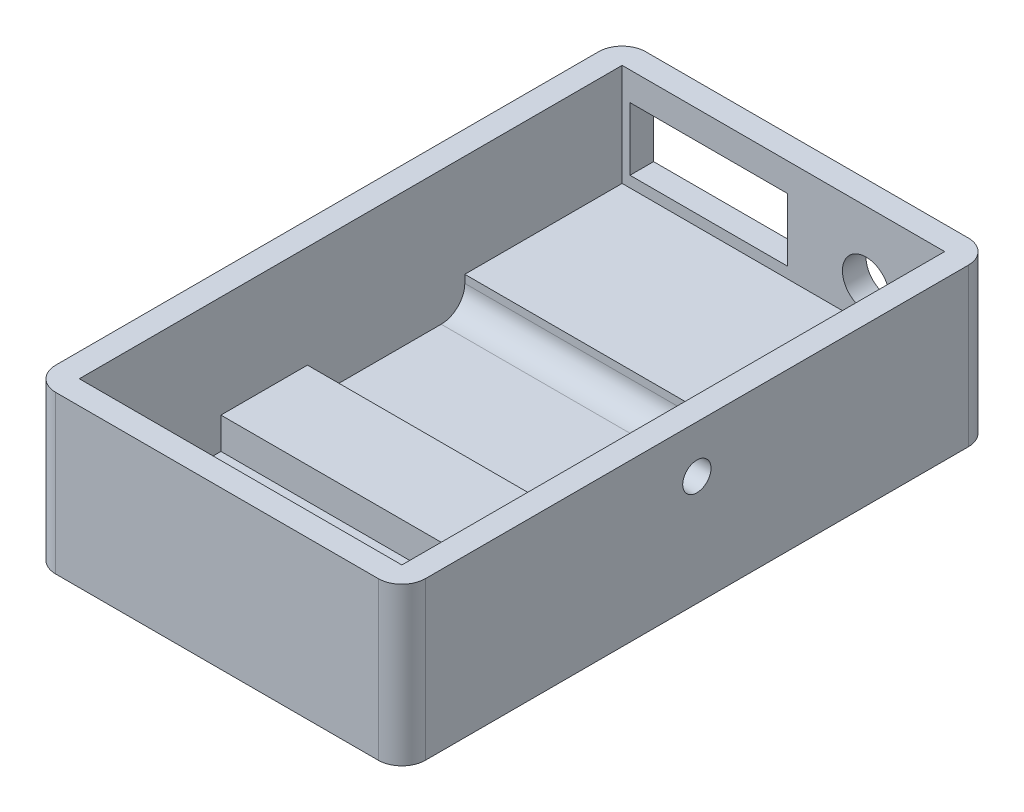
SolidWorks part; units mm, degrees
ref_plane "前视基准面" through (0, 0, 0) normal (0, 0, 1) x (1, 0, 0)
ref_plane "上视基准面" through (0, 0, 0) normal (0, 1, 0) x (1, 0, 0)
ref_plane "右视基准面" through (0, 0, 0) normal (1, 0, 0) x (0, 0, -1)
sketch "草图2" plane through (0, 0, 0) normal (0, 1, 0) x (1, 0, 0)
  line L1 (-11.75, 18.75) -> (11.75, 18.75)
  line L2 (-11.75, 18.75) -> (-11.75, -18.75)
  line L3 (-11.75, -18.75) -> (11.75, -18.75)
  line L4 (11.75, 18.75) -> (11.75, -18.75)
  dimension "D1" = 23.5
  dimension "D2" = 37.5
  dimension "D3" = 18.75
  dimension "D4" = 11.75
extrude "凸台-拉伸1" add sketch "草图2" along normal blind 10
shell "抽壳1" thickness 1.5
fillet "圆角1" radius 1.5 4 edges at (11.75, 5, -18.75) (11.75, 5, 18.75) (-11.75, 5, 18.75) (-11.75, 5, -18.75)
sketch "草图3" plane through (0, 1.5, 0) normal (0, 1, 0) x (1, 0, 0)
  line L0 (-10.25, 17.25) -> (-10.25, -17.25) construction
  line L1 (-10.25, 17.25) -> (10.25, 17.25)
  line L2 (-10.25, 17.25) -> (-10.25, -8.25)
  line L3 (-10.25, -8.25) -> (10.25, -8.25)
  line L4 (10.25, 17.25) -> (10.25, -8.25)
  line L5 (10.25, -17.25) -> (10.25, 17.25) construction
  line L6 (-10.25, -17.25) -> (10.25, -17.25) construction
  dimension "D1" = 9
extrude "凸台-拉伸2" add sketch "草图3" along normal blind 2
sketch "草图4" plane through (0, 3.5, 0) normal (0, 1, 0) x (1, 0, 0)
  line L0 (-10.25, 17.25) -> (-10.25, -17.25) construction
  line L1 (-10.25, 7.25) -> (10.25, 7.25)
  line L2 (-10.25, 7.25) -> (-10.25, -2.75)
  line L3 (-10.25, -2.75) -> (10.25, -2.75)
  line L4 (10.25, 7.25) -> (10.25, -2.75)
  line L5 (10.25, -17.25) -> (10.25, 17.25) construction
  dimension "D1" = 10
  dimension "D2" = 10
extrude "切除-拉伸1" cut sketch "草图4" against normal blind 2
fillet "圆角2" radius 1.5 2 edges at (0, 1.5, 2.75) (0, 1.5, -7.25)
sketch "草图6" plane through (0, 0, -18.75) normal (0, 0, -1) x (-1, 0, 0)
  line L0 (10.25, 0) -> (10.25, 10) construction
  line L1 (-0.25, 8.2) -> (9.75, 8.2)
  line L2 (-0.25, 8.2) -> (-0.25, 4.2)
  line L3 (-0.25, 4.2) -> (9.75, 4.2)
  line L4 (9.75, 8.2) -> (9.75, 4.2)
  line L5 (-10.25, 0) -> (10.25, 0) construction
  dimension "D1" = 10
  dimension "D2" = 0.5
  dimension "D3" = 4
  dimension "D4" = 4.2
extrude "切除-拉伸2" cut sketch "草图6" against normal blind 2
sketch "草图7" plane through (0, 0, -18.75) normal (0, 0, -1) x (-1, 0, 0)
  line L0 (-0.25, 8.2) -> (-0.25, 4.2) construction
  circle A0 centre (-5.25, 5.7) radius 1.5
  dimension "D2" = 3
  dimension "D1" = 5
  dimension "D3" = 1.5
extrude "切除-拉伸3" cut sketch "草图7" against normal blind 2
sketch "草图8" plane through (0, 3.5, 0) normal (0, 1, 0) x (1, 0, 0)
  line L0 (10.25, 17.25) -> (-10.25, 17.25) construction
  line L1 (10.25, -17.25) -> (10.25, 17.25) construction
  circle A0 centre (7.85, 10.85) radius 0.9
  dimension "D3" = 1.8
  dimension "D1" = 6.4
  dimension "D2" = 2.4
extrude "切除-拉伸4" cut sketch "草图8" against normal blind 3
sketch "草图9" plane through (11.75, 0, 0) normal (1, 0, 0) x (0, 0, -1)
  line L0 (-17.25, 10) -> (17.25, 10) construction
  circle A0 centre (0, 7) radius 0.9
  dimension "D1" = 3
extrude "切除-拉伸5" cut sketch "草图9" against normal blind 3
